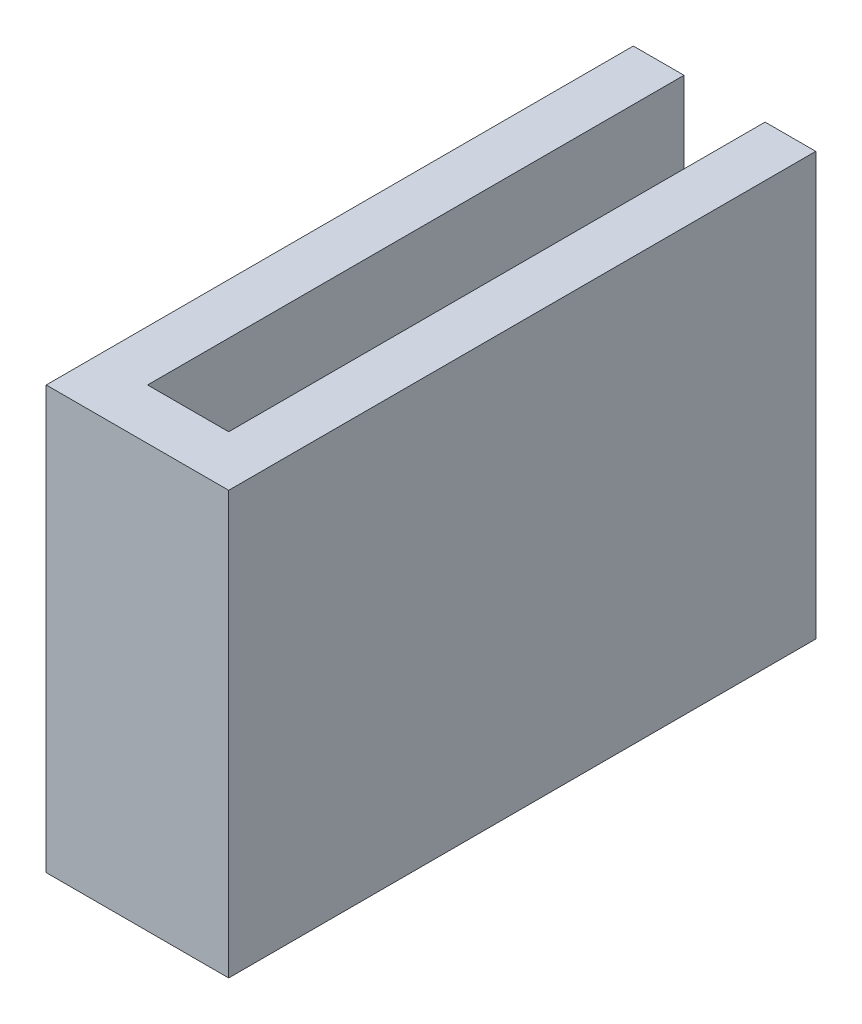
SolidWorks part; units mm, degrees
ref_plane "Front Plane" through (0, 0, 0) normal (0, 0, 1) x (1, 0, 0)
ref_plane "Top Plane" through (0, 0, 0) normal (0, 1, 0) x (1, 0, 0)
ref_plane "Right Plane" through (0, 0, 0) normal (1, 0, 0) x (0, 0, -1)
sketch "Sketch1" plane through (0, 0, 0) normal (0, 1, 0) x (1, 0, 0)
  line L0 (0, 0) -> (0, 34.75)
  line L1 (0, 34.75) -> (3, 34.75)
  line L2 (3, 34.75) -> (3, 3)
  line L3 (3, 3) -> (7.8, 3)
  line L4 (7.8, 3) -> (7.8, 34.75)
  line L5 (7.8, 34.75) -> (10.8, 34.75)
  line L6 (10.8, 34.75) -> (10.8, 0)
  line L7 (10.8, 0) -> (0, 0)
  point P9 (7.8, 18.875)
  dimension "D1" = 4.8
  dimension "D2" = 3
  dimension "D3" = 3
  dimension "D4" = 31.75
  dimension "D5" = 3
extrude "Boss-Extrude1" add sketch "Sketch1" along normal blind 25
